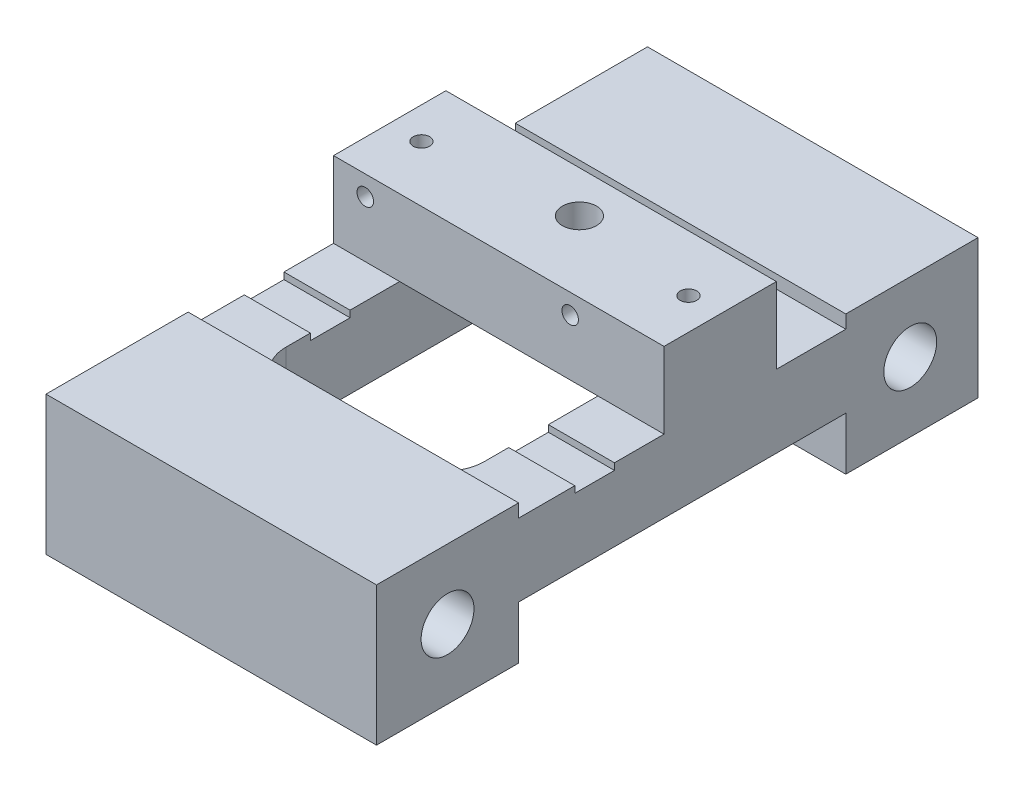
SolidWorks part; units mm, degrees
ref_plane "Front Plane" through (0, 0, 0) normal (0, 0, 1) x (1, 0, 0)
ref_plane "Top Plane" through (0, 0, 0) normal (0, 1, 0) x (1, 0, 0)
ref_plane "Right Plane" through (0, 0, 0) normal (1, 0, 0) x (0, 0, -1)
sketch "Sketch1" plane through (0, 0, 0) normal (1, 0, 0) x (0, 0, -1)
  line L0 (0, 0) -> (0, 21)
  line L1 (0, 21) -> (21.5, 21)
  line L2 (21.5, 21) -> (21.5, 19)
  line L3 (21.5, 19) -> (30, 19)
  line L4 (30, 19) -> (30, 18)
  line L5 (30, 18) -> (36, 18)
  line L6 (36, 18) -> (36, 19)
  line L7 (36, 19) -> (43.5, 19)
  line L8 (43.5, 19) -> (43.5, 30.5)
  line L9 (43.5, 30.5) -> (60.5, 30.5)
  line L10 (60.5, 30.5) -> (60.5, 19)
  line L11 (60.5, 19) -> (71, 19)
  line L12 (71, 19) -> (71, 21)
  line L13 (71, 21) -> (91, 21)
  line L14 (91, 21) -> (91, 0)
  line L15 (91, 0) -> (71, 0)
  line L16 (71, 0) -> (71, 8)
  line L17 (71, 8) -> (21.5, 8)
  line L18 (21.5, 8) -> (21.5, 0)
  line L19 (21.5, 0) -> (0, 0)
  dimension "D1" = 21.5
  dimension "D2" = 20
  dimension "D3" = 91
  dimension "D4" = 17
  dimension "D5" = 6
  dimension "D6" = 8.5
  dimension "D7" = 7.5
  dimension "D8" = 10.5
  dimension "D9" = 21
  dimension "D10" = 11
  dimension "D11" = 22.5
  dimension "D12" = 1
  dimension "D13" = 2
extrude "Boss-Extrude1" add sketch "Sketch1" along normal blind 50
sketch "Sketch2" plane through (0, 8, 0) normal (0, 1, 0) x (1, 0, 0)
  line L0 (50, 0) -> (0, 0) construction
  line L1 (16, 71.3) -> (34, 71.3)
  line L2 (10, 65.3) -> (10, 26.3)
  line L3 (16, 20.3) -> (34, 20.3)
  line L4 (40, 65.3) -> (40, 26.3)
  line L5 (0, 91) -> (50, 91) construction
  arc A0 (34, 20.3) -> (40, 26.3) centre (34, 26.3) ccw
  arc A1 (10, 26.3) -> (16, 20.3) centre (16, 26.3) ccw
  arc A2 (34, 71.3) -> (40, 65.3) centre (34, 65.3) cw
  arc A3 (16, 71.3) -> (10, 65.3) centre (16, 65.3) ccw
  point P6 (25, 91)
  point P11 (25, 20.3)
  point P16 (10, 20.3)
  point P19 (40, 71.3)
  point P22 (10, 71.3)
  dimension "D4" = 6
  dimension "D1" = 30
  dimension "D2" = 51
  dimension "D3" = 20.3
extrude "Cut-Extrude1" cut sketch "Sketch2" along normal up to surface (11 mm away) up to face at (25, 19, -65.75)
hole_wizard "M3 Tapped Hole1" positions "Sketch3" profile "Sketch4" tap size "M3" standard "ISO" end condition through all
sketch "Sketch3" plane through (0, 30.5, 0) normal (0, 1, 0) x (1, 0, 0)
  line L0 (0, 60.5) -> (0, 43.5) construction
  line L1 (50, 60.5) -> (50, 43.5) construction
  line L2 (50, 60.5) -> (50, 43.5) construction
  point P0 (4.8, 52)
  point P2 (45.2, 52)
  point P21 (50, 52)
  dimension "D1" = 4.8
  dimension "D2" = 4.8
cosmetic thread "Hole Thread1" parameters "D2"=3
cosmetic thread "Hole Thread2" parameters "D2"=3
sketch "Sketch4" plane through (4.8, 30.5, -52) normal (1, 0, 0) x (0, 0, 1)
  line L0 (0, 0) -> (0, 30.5)
  line L1 (0, 30.5) -> (1.25, 30.5)
  line L2 (1.25, 30.5) -> (1.25, 0)
  line L5 (1.25, 0) -> (0, 0)
  line L11 (0, -6.35) -> (0, 107.95) construction
  dimension "Thru Tap Drill Dia." = 2.5
  dimension "Thru Tap Drill Depth" = 30.5
hole_wizard "M3 Tapped Hole2" positions "Sketch5" profile "Sketch6" tap size "M3" standard "ISO" end condition through all
sketch "Sketch5" plane through (0, 0, -60.5) normal (0, 0, -1) x (-1, 0, 0)
  line L1 (0, 19) -> (0, 30.5) construction
  line L2 (-50, 30.5) -> (0, 30.5) construction
  point P0 (-4.8, 27.5)
  point P2 (-35.8, 27.5)
  dimension "D1" = 31
  dimension "D2" = 4.8
  dimension "D3" = 3
sketch "Sketch6" plane through (4.8, 27.5, -60.5) normal (1, 0, 0) x (0, 1, 0)
  line L0 (0, 0) -> (0, 60.5)
  line L1 (0, 60.5) -> (1.25, 60.5)
  line L2 (1.25, 60.5) -> (1.25, 0)
  line L5 (1.25, 0) -> (0, 0)
  line L11 (0, -6.35) -> (0, 107.95) construction
  dimension "Thru Tap Drill Dia." = 2.5
  dimension "Thru Tap Drill Depth" = 60.5
cosmetic thread "Hole Thread4" parameters "D2"=3
cosmetic thread "Hole Thread5" parameters "D2"=3
sketch "Sketch7" plane through (0, 30.5, 0) normal (0, 1, 0) x (1, 0, 0)
  line L0 (50, 60.5) -> (50, 43.5) construction
  line L2 (50, 60.5) -> (0, 60.5) construction
  circle A0 centre (26.5, 54.2) radius 2.5772
  dimension "D1" = 23.5
  dimension "D2" = 6.3
extrude "Cut-Extrude2" cut sketch "Sketch7" against normal through all
sketch "Sketch8" plane through (50, 0, 0) normal (1, 0, 0) x (0, 0, -1)
  line L0 (0, 0) -> (21.5, 0) construction
  line L1 (0, 21) -> (0, 0) construction
  circle A0 centre (10.75, 10.5) radius 4
  circle A1 centre (80.75, 10.5) radius 4
  point P4 (0, 0)
  point P5 (10.5595, 10.6398)
  point P8 (10.75, 0)
  point P11 (0, 10.5)
  dimension "D1" = 8
  dimension "70" = 70
extrude "Cut-Extrude3" cut sketch "Sketch8" against normal up to next and the other way through all
